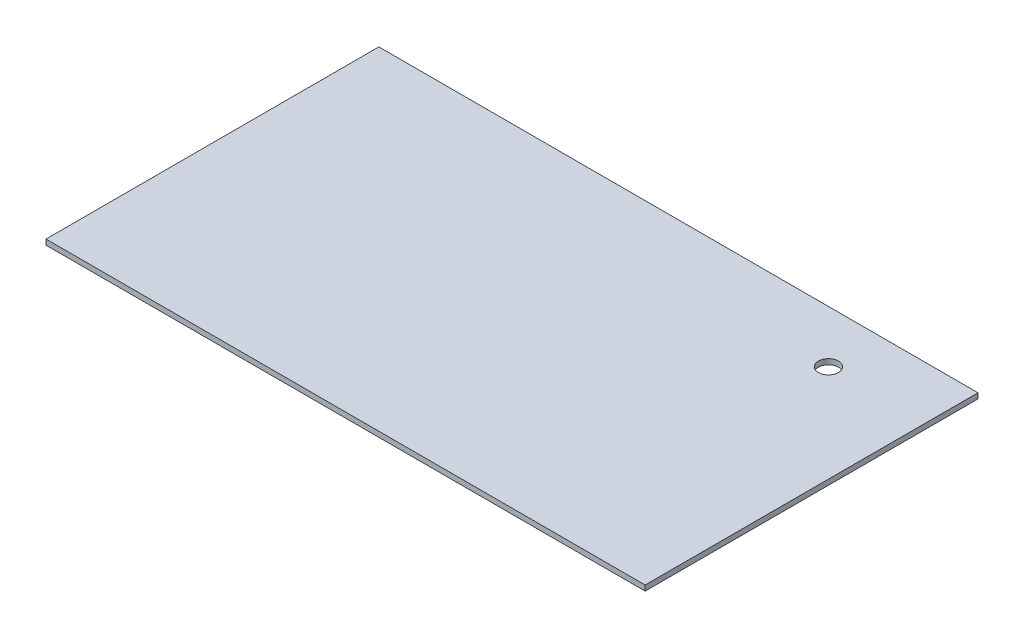
SolidWorks part; units mm, degrees
ref_plane "前基準面" through (0, 0, 0) normal (0, 0, 1) x (1, 0, 0)
ref_plane "上基準面" through (0, 0, 0) normal (0, 1, 0) x (1, 0, 0)
ref_plane "右基準面" through (0, 0, 0) normal (1, 0, 0) x (0, 0, -1)
sketch "草圖1" plane through (0, 0, 0) normal (0, 1, 0) x (1, 0, 0)
  line L0 (0, 0) -> (450, 0)
  line L1 (450, 0) -> (450, 250)
  line L2 (450, 250) -> (0, 250)
  line L3 (0, 250) -> (0, 0)
  dimension "D1" = 450
  dimension "D2" = 250
extrude "填料-伸長1" add sketch "草圖1" along normal blind 4
sketch "草圖2" plane through (0, 4, 0) normal (0, 1, 0) x (1, 0, 0)
  line L0 (450, 250) -> (0, 250) construction
  line L1 (450, 0) -> (450, 250) construction
  circle A0 centre (376.92, 210.73) radius 7.5
  dimension "D1" = 39.27
  dimension "D2" = 73.08
  dimension "D3" = 15
extrude "除料-伸長1" cut sketch "草圖2" against normal through all
